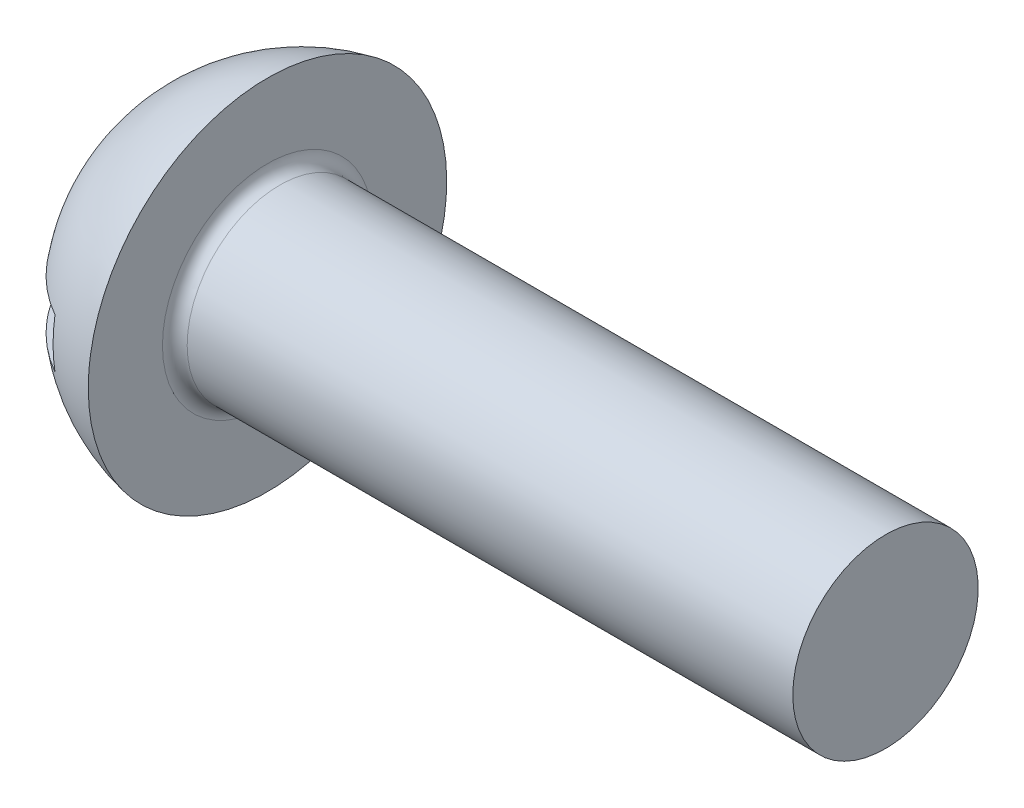
SolidWorks part; units mm, degrees
ref_plane "前视基准面" through (0, 0, 0) normal (0, 0, 1) x (1, 0, 0)
ref_plane "上视基准面" through (0, 0, 0) normal (0, 1, 0) x (1, 0, 0)
ref_plane "右视基准面" through (0, 0, 0) normal (1, 0, 0) x (0, 0, -1)
sketch "草图1" plane through (0, 0, 0) normal (0, 0, 1) x (1, 0, 0)
  line L0 (0, 0) -> (1.5, 0) construction
  line L1 (2.4, 2.9) -> (2.4, 1.5)
  line L2 (2.4, 1.5) -> (6.4, 1.5)
  line L3 (6.4, 1.5) -> (12.4, 1.5)
  line L4 (12.4, 1.5) -> (12.4, 0)
  line L5 (12.4, 0) -> (0, 0)
  line L6 (1.5, 0.4) -> (1.5, -0.4) construction
  line L7 (12.4, 0) -> (12.6, 0) construction
  arc A0 (0, 0) -> (2.4, 2.9) centre (2.9521, 0) cw
  dimension "k" = 2.4
  dimension "l" = 10
  dimension "d" = 3
  dimension "dk" = 5.8
  dimension "l0" = 6
  dimension "n" = 0.8
  dimension "t" = 1.5
  dimension "r" = 0.2
revolve "旋转1" add sketch "草图1" angle 360 about L0
cosmetic thread "装饰螺纹线1" parameters "D1"=6, "D2"=2.598
sketch "草图2" plane through (0, 0, 0) normal (1, 0, 0) x (0, 0, -1)
  line L0 (2.9, 0.4) -> (-2.9, 0.4)
  line L1 (-2.9, 0.4) -> (-2.9, -0.4)
  line L2 (-2.9, -0.4) -> (2.9, -0.4)
  line L3 (2.9, -0.4) -> (2.9, 0.4)
  circle A1 centre (0, 0) radius 2.9 construction
extrude "切除-拉伸1" cut sketch "草图2" along normal up to vertex (1.5 mm away) up to point (1.5, 0.4, 0)
fillet "圆角1" radius 0.2 1 edges at (2.4, 0, 1.5)
equation "\"D2@装饰螺纹线1\" = \"d@草图1\"*0.866"
equation "\"D1@装饰螺纹线1\" =\"l0@草图1\""
equation "\"D1@圆角1\" = \"r@草图1\""
